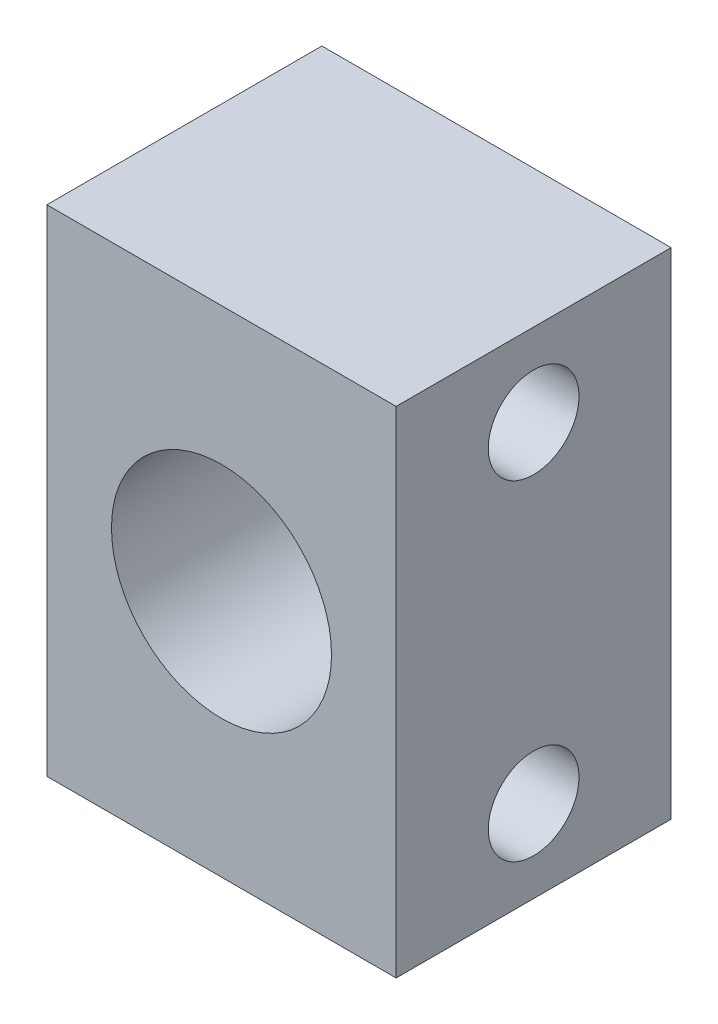
SolidWorks part; units mm, degrees
ref_plane "Alzado" through (0, 0, 0) normal (0, 0, 1) x (1, 0, 0)
ref_plane "Planta" through (0, 0, 0) normal (0, 1, 0) x (1, 0, 0)
ref_plane "Vista lateral" through (0, 0, 0) normal (1, 0, 0) x (0, 0, -1)
sketch "Croquis1" plane through (0, 0, 0) normal (1, 0, 0) x (0, 0, -1)
  line L1 (-5, -9) -> (5, -9)
  line L2 (-5, -9) -> (-5, 9)
  line L3 (-5, 9) -> (5, 9)
  line L4 (5, -9) -> (5, 9)
  line L5 (-5, -9) -> (5, 9) construction
  line L6 (-5, 9) -> (5, -9) construction
  point P0 (0, 0)
  dimension "D1" = 18
  dimension "D2" = 10
extrude "Saliente-Extruir1" add sketch "Croquis1" along normal mid plane 12.7
hole_wizard "Taladro roscado M4x0.71" positions "Croquis2" profile "Croquis3" tap size "M4x0.7" standard "Ansi Metric" end condition up to next
sketch "Croquis2" plane through (6.35, 0, 0) normal (1, 0, 0) x (0, 0, -1)
  line L0 (0, 6) -> (0, -6) construction
  point P0 (0, 6)
  point P2 (0, -6)
  point P12 (0, 0)
  dimension "D1" = 12
sketch "Croquis3" plane through (6.35, 6, 0) normal (0, 1, 0) x (0, 0, -1)
  line L0 (0, 0) -> (0, 12.7)
  line L1 (0, 12.7) -> (1.65, 12.7)
  line L2 (1.65, 12.7) -> (1.65, 0)
  line L5 (1.65, 0) -> (0, 0)
  line L11 (0, -6.35) -> (0, 107.95) construction
  dimension "Diámetro de perforador para roscar hasta el siguiente" = 3.3
  dimension "Profundidad de perforador para roscar hasta el siguiente" = 12.7
cosmetic thread "Rosca de taladro1" parameters "D2"=4
cosmetic thread "Rosca de taladro2" parameters "D2"=4
hole_wizard "Diámetro de taladro Ø5.0 (5)1" positions "Croquis4" profile "Croquis5" hole size "Ø5.0" standard "Ansi Metric" end condition up to next
sketch "Croquis4" plane through (0, 0, 5) normal (0, 0, 1) x (1, 0, 0)
  point P0 (0, 0)
sketch "Croquis5" plane through (0, 0, 5) normal (1, 0, 0) x (0, -1, 0)
  line L0 (0, 0) -> (0, 10)
  line L1 (0, 10) -> (4, 10)
  line L2 (4, 10) -> (4, 0)
  line L5 (4, 0) -> (0, 0)
  line L11 (0, -6.35) -> (0, 107.95) construction
  dimension "Diámetro de taladro hasta el siguiente" = 8
  dimension "Profundidad de taladro hasta el siguiente" = 10
